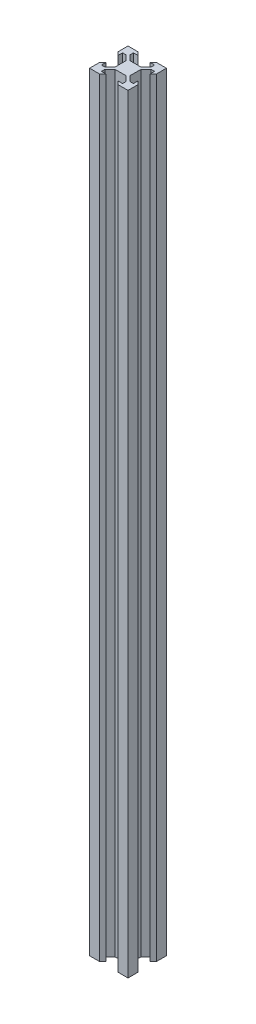
SolidWorks part; units mm, degrees
ref_plane "Front Plane" through (0, 0, 0) normal (0, 0, 1) x (1, 0, 0)
ref_plane "Top Plane" through (0, 0, 0) normal (0, 1, 0) x (1, 0, 0)
ref_plane "Right Plane" through (0, 0, 0) normal (1, 0, 0) x (0, 0, -1)
sketch "Sketch1" plane through (0, 0, 0) normal (0, 1, 0) x (1, 0, 0)
  line L88 (2.8343, 3.894) -> (-2.8343, 3.894)
  line L89 (-2.8343, 3.894) -> (-5.5, 6.5588)
  line L90 (-5.5, 6.5588) -> (-5.5, 8.3491)
  line L91 (-5.5, 8.3491) -> (-3.1, 8.3491)
  line L92 (-3.1, 8.3491) -> (-4.75, 9.9986)
  line L93 (-4.75, 9.9986) -> (-10, 9.9986)
  line L94 (-10, 9.9986) -> (-10, 4.747)
  line L95 (-10, 4.747) -> (-8.35, 3.0975)
  line L96 (-8.35, 3.0975) -> (-8.3507, 5.4975)
  line L97 (-8.3507, 5.4975) -> (-6.5605, 5.498)
  line L98 (-6.5605, 5.498) -> (-3.8948, 2.8332)
  line L99 (-3.8948, 2.8332) -> (-3.8948, -2.8332)
  line L100 (-3.8948, -2.8332) -> (-6.5605, -5.498)
  line L101 (-6.5605, -5.498) -> (-8.3507, -5.4975)
  line L102 (-8.3507, -5.4975) -> (-8.35, -3.0975)
  line L103 (-8.35, -3.0975) -> (-10, -4.747)
  line L104 (-10, -4.747) -> (-10, -9.9986)
  line L105 (-10, -9.9986) -> (-4.75, -9.9986)
  line L106 (-4.75, -9.9986) -> (-3.1, -8.3491)
  line L107 (-3.1, -8.3491) -> (-5.5, -8.3491)
  line L108 (-5.5, -8.3491) -> (-5.5, -6.5588)
  line L109 (-5.5, -6.5588) -> (-2.8343, -3.894)
  line L110 (-2.8343, -3.894) -> (2.8343, -3.894)
  line L111 (2.8343, -3.894) -> (5.5, -6.5588)
  line L112 (5.5, -6.5588) -> (5.5, -8.3491)
  line L113 (5.5, -8.3491) -> (3.1, -8.3491)
  line L114 (3.1, -8.3491) -> (4.75, -9.9986)
  line L115 (4.75, -9.9986) -> (10, -9.9986)
  line L116 (10, -9.9986) -> (10, -4.747)
  line L117 (10, -4.747) -> (8.35, -3.0975)
  line L118 (8.35, -3.0975) -> (8.3507, -5.4975)
  line L119 (8.3507, -5.4975) -> (6.5605, -5.498)
  line L120 (6.5605, -5.498) -> (3.8948, -2.8332)
  line L121 (3.8948, -2.8332) -> (3.8948, 2.8332)
  line L122 (3.8948, 2.8332) -> (6.5605, 5.498)
  line L123 (6.5605, 5.498) -> (8.3507, 5.4975)
  line L124 (8.3507, 5.4975) -> (8.35, 3.0975)
  line L125 (8.35, 3.0975) -> (10, 4.747)
  line L126 (10, 4.747) -> (10, 9.9986)
  line L127 (10, 9.9986) -> (4.75, 9.9986)
  line L128 (4.75, 9.9986) -> (3.1, 8.3491)
  line L129 (3.1, 8.3491) -> (5.5, 8.3491)
  line L130 (5.5, 8.3491) -> (5.5, 6.5588)
  line L131 (5.5, 6.5588) -> (2.8343, 3.894)
  dimension "D2" = 5.25
  dimension "D3" = 19.9971
  dimension "D4" = 20
extrude "Boss-Extrude1" add sketch "Sketch1" along normal blind 400
